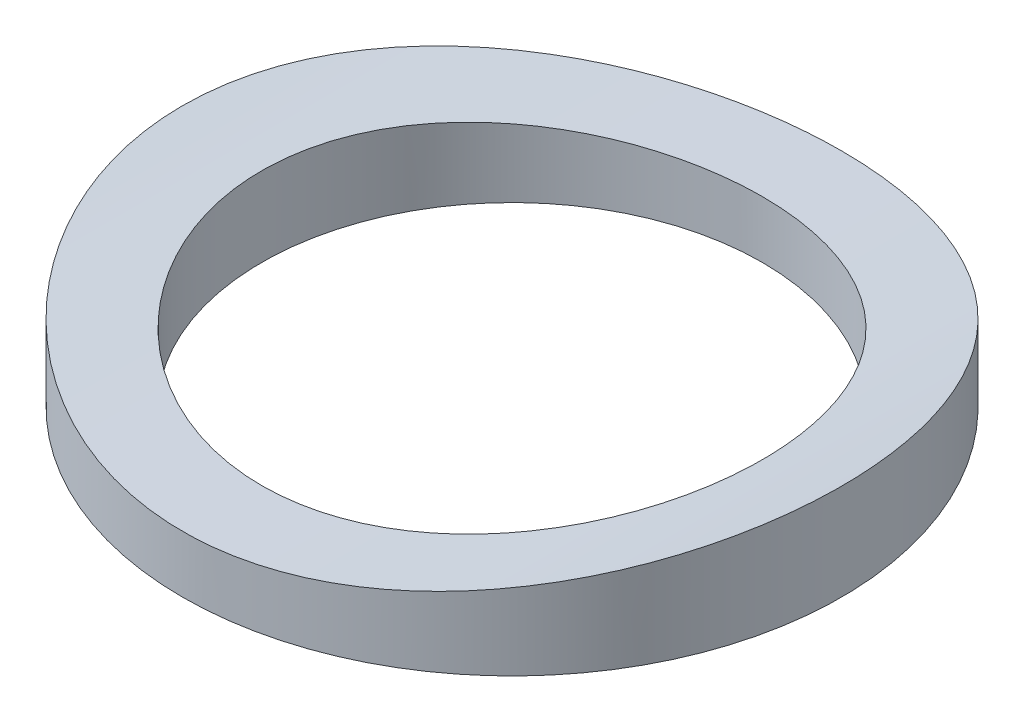
SolidWorks part; units mm, degrees
ref_plane "Front Plane" through (0, 0, 0) normal (0, 0, 1) x (1, 0, 0)
ref_plane "Top Plane" through (0, 0, 0) normal (0, 1, 0) x (1, 0, 0)
ref_plane "Right Plane" through (0, 0, 0) normal (1, 0, 0) x (0, 0, -1)
sketch "Sketch1" plane through (0, 0, 0) normal (0, 1, 0) x (1, 0, 0)
  circle A0 centre (0, 0) radius 10.4
  circle A1 centre (0, 0) radius 7.9
  dimension "D1" = 15.8
  dimension "D2" = 20.8
extrude "Boss-Extrude1" add sketch "Sketch1" along normal blind 3.2
sketch "Sketch4" plane through (0, 0, 0) normal (0, 0, 1) x (1, 0, 0)
  line L2 (-10.4, 0) -> (10.4, 0) construction
  circle A0 centre (0, 46.25) radius 44.45
  dimension "D1" = 88.9
  dimension "D2" = 46.25
surface "Surface-Extrude1" sketch "Sketch4" parameters "D1"=30
other "SurfaceCut5"
